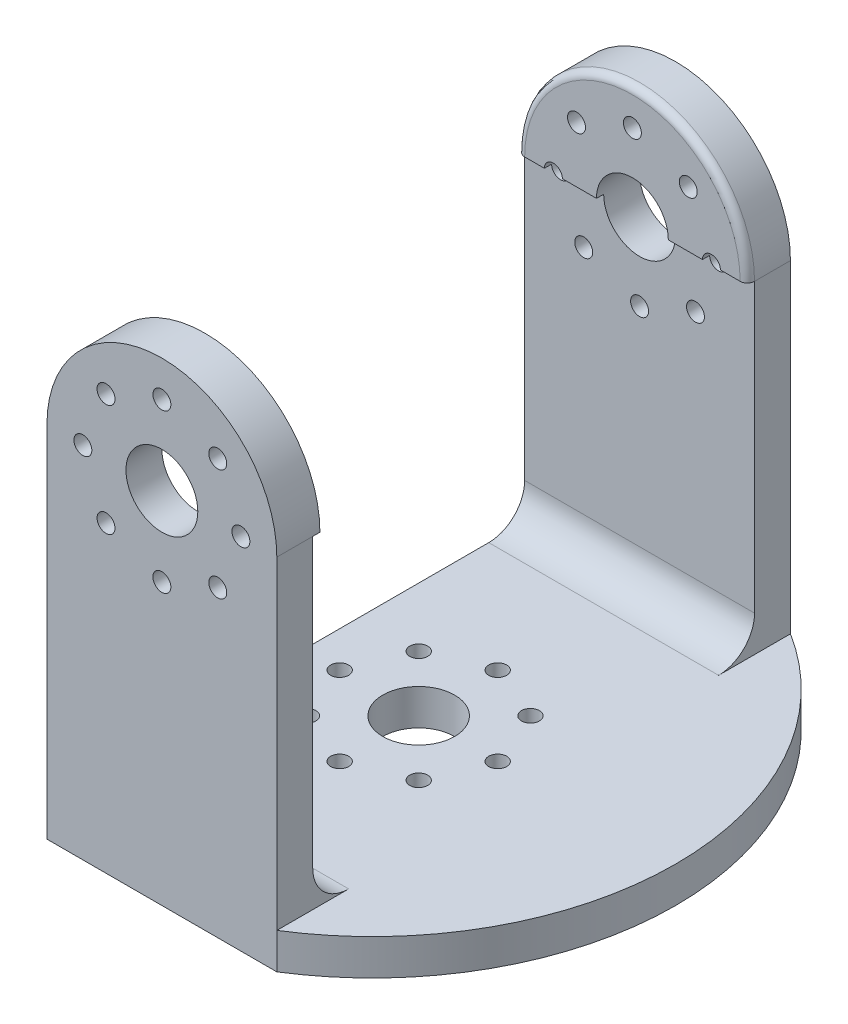
SolidWorks part; units mm, degrees
ref_plane "Front Plane" through (0, 0, 0) normal (0, 0, 1) x (1, 0, 0)
ref_plane "Top Plane" through (0, 0, 0) normal (0, 1, 0) x (1, 0, 0)
ref_plane "Right Plane" through (0, 0, 0) normal (1, 0, 0) x (0, 0, -1)
sketch "Sketch1" plane through (0, 0, 0) normal (0, 1, 0) x (1, 0, 0)
  line L1 (-17.1012, 48.8927) -> (14.8988, 48.8927)
  line L2 (-17.1012, 48.8927) -> (-17.1012, -22.6073)
  line L3 (-17.1012, -22.6073) -> (14.8988, -22.6073)
  line L4 (14.8988, 48.8927) -> (14.8988, -22.6073)
  dimension "D1" = 32
  dimension "D2" = 71.5
extrude "Boss-Extrude1" add sketch "Sketch1" along normal blind 5
sketch "Sketch2" plane through (0, 5, 0) normal (0, 1, 0) x (1, 0, 0)
  line L0 (-17.1012, 48.8927) -> (-17.1012, -22.6073) construction
  line L1 (-17.1012, -17.6073) -> (14.8988, -17.6073)
  line L2 (-17.1012, -17.6073) -> (-17.1012, -22.6073)
  line L3 (-17.1012, -22.6073) -> (14.8988, -22.6073)
  line L4 (14.8988, -17.6073) -> (14.8988, -22.6073)
  dimension "D1" = 5
extrude "Boss-Extrude2" add sketch "Sketch2" along normal blind 45
ref_plane "Plane1" through (0, 0, -13.1427) normal (0, 0, -1) x (-1, 0, 0)
mirror "Mirror1" about plane through (0, 0, -13.1427) normal (0, 0, -1) of "Boss-Extrude1", "Boss-Extrude2"
sketch "Sketch3" plane through (0, 0, 22.6073) normal (0, 0, 1) x (1, 0, 0)
  line L0 (-17.1012, 50) -> (14.8988, 50)
  arc A0 (-17.1012, 50) -> (14.8988, 50) centre (-1.1012, 50) cw
extrude "Boss-Extrude3" add sketch "Sketch3" against normal blind 6
mirror "Mirror3" about plane through (0, 0, -13.1427) normal (0, 0, -1) of "Boss-Extrude3"
sketch "Sketch4" plane through (0, 0, 22.6073) normal (0, 0, 1) x (1, 0, 0)
  line L0 (-17.1012, 50) -> (14.8988, 50) construction
  circle A0 centre (-1.1012, 50) radius 5
  circle A1 centre (-1.1012, 61) radius 1.25
  circle A2 centre (6.677, 57.7782) radius 1.25
  circle A3 centre (9.8988, 50) radius 1.25
  circle A4 centre (6.677, 42.2218) radius 1.25
  circle A5 centre (-1.1012, 39) radius 1.25
  circle A6 centre (-8.8794, 42.2218) radius 1.25
  circle A7 centre (-12.1012, 50) radius 1.25
  circle A8 centre (-8.8794, 57.7782) radius 1.25
  point P24 (-1.1012, 50)
  dimension "D1" = 8
  dimension "D2" = 11
extrude "Cut-Extrude1" cut sketch "Sketch4" against normal through all
sketch "Sketch5" plane through (0, 0, 0) normal (0, -1, 0) x (-1, 0, 0)
  line L0 (-14.8988, 13.1427) -> (17.1012, 13.1427) construction
  line L1 (-6.677, 20.9209) -> (8.8794, 20.9209) construction
  circle A10 centre (1.1012, 13.1427) radius 5
  circle A11 centre (1.1012, 24.1427) radius 1.25
  circle A12 centre (8.8794, 20.9209) radius 1.25
  circle A13 centre (12.1012, 13.1427) radius 1.25
  circle A14 centre (8.8794, 5.3645) radius 1.25
  circle A15 centre (1.1012, 2.1427) radius 1.25
  circle A16 centre (-6.677, 5.3645) radius 1.25
  circle A17 centre (-9.8988, 13.1427) radius 1.25
  circle A18 centre (-6.677, 20.9209) radius 1.25
  point P22 (1.1012, 13.1427)
  dimension "D1" = 11
extrude "Cut-Extrude2" cut sketch "Sketch5" against normal through all
fillet "Fillet1" radius 5 2 edges at (-1.1012, 5, -43.8927) (-1.1012, 5, 17.6073)
sketch "Sketch6" plane through (0, 0, 0) normal (0, -1, 0) x (1, 0, 0)
  line L0 (14.8988, 22.6073) -> (14.8988, -48.8927)
  arc A0 (14.8988, 22.6073) -> (14.8988, -48.8927) centre (-7.5508, -13.1427) cw
extrude "Boss-Extrude4" add sketch "Sketch6" against normal blind 5
fillet "Fillet2" radius 1 1 edges at (-1.1012, 66, -42.8927)
